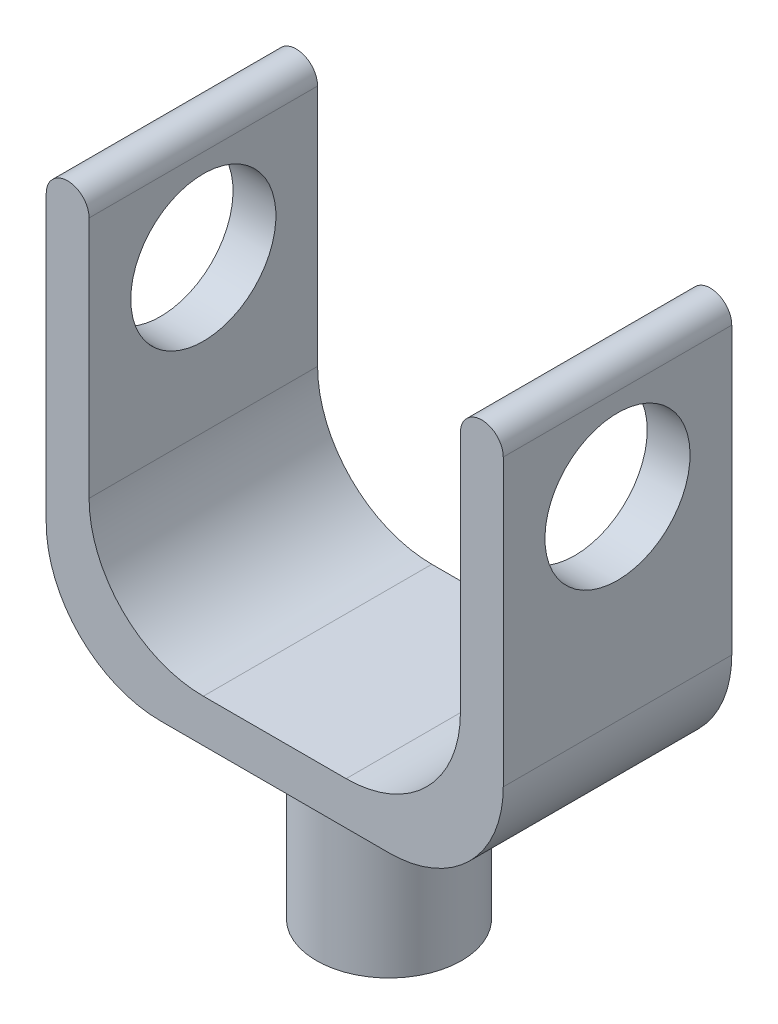
SolidWorks part; units mm, degrees
material "AISI 1020 Steel, Cold Rolled"
ref_plane "Front Plane" through (0, 0, 0) normal (0, 0, 1) x (1, 0, 0)
ref_plane "Top Plane" through (0, 0, 0) normal (0, 1, 0) x (1, 0, 0)
ref_plane "Right Plane" through (0, 0, 0) normal (1, 0, 0) x (0, 0, -1)
sketch "Sketch1" plane through (0, 0, 0) normal (0, 0, 1) x (1, 0, 0)
  line L0 (-40, 70) -> (-40, 0)
  line L1 (-40, 0) -> (40, 0)
  line L2 (40, 0) -> (40, 70)
  line L3 (0, 78.3803) -> (0, -68.5211) construction
  line L7 (-32.5, 70) -> (-32.5, 7.5)
  line L8 (-32.5, 7.5) -> (32.5, 7.5)
  line L9 (32.5, 7.5) -> (32.5, 70)
  arc A2 (-40, 70) -> (-32.5, 70) centre (-36.25, 70) cw
  arc A3 (40, 70) -> (32.5, 70) centre (36.25, 70) ccw
  dimension "D1" = 70
  dimension "D2" = 80
  dimension "D3" = 7.5
extrude "Boss-Extrude1" add sketch "Sketch1" along normal mid plane 40
ref_plane "Plane1" through (0, 0, 0) normal (0, -1, 0) x (-1, 0, 0)
sketch "Sketch2" plane through (0, 0, 0) normal (0, -1, 0) x (-1, 0, 0)
  circle A0 centre (0, 0) radius 12.7
  dimension "D1" = 25.4
extrude "Boss-Extrude2" add sketch "Sketch2" along normal blind 30
fillet "Fillet1" radius 20 4 edges at (40, 0, 0) (-40, 0, 0) (-32.5, 7.5, 0) (32.5, 7.5, 0)
ref_plane "Plane2" through (-40, 0, 0) normal (-1, 0, 0) x (0, 0, 1)
sketch "Sketch3" plane through (-40, 0, 0) normal (-1, 0, 0) x (0, 0, 1)
  circle A0 centre (0, 54) radius 12.7
  dimension "D1" = 25.4
  dimension "D2" = 54
extrude "Cut-Extrude1" cut sketch "Sketch3" against normal through all both and the other way through all
